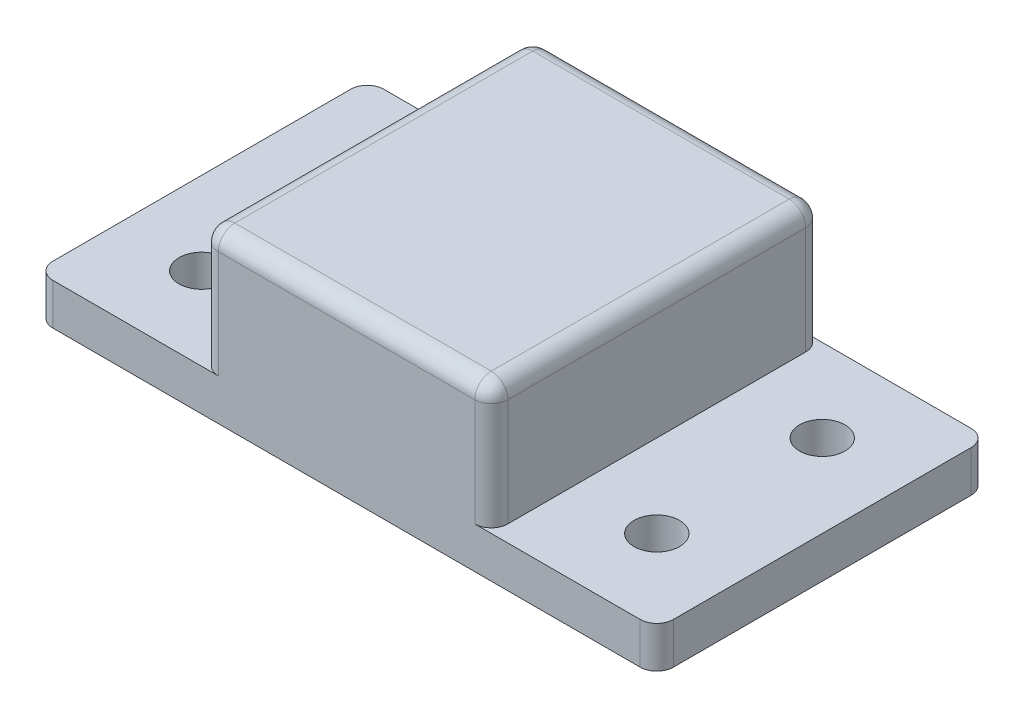
SolidWorks part; units mm, degrees
ref_plane "Front Plane" through (0, 0, 0) normal (0, 0, 1) x (1, 0, 0)
ref_plane "Top Plane" through (0, 0, 0) normal (0, 1, 0) x (1, 0, 0)
ref_plane "Right Plane" through (0, 0, 0) normal (1, 0, 0) x (0, 0, -1)
sketch "Sketch1" plane through (0, 0, 0) normal (0, 1, 0) x (1, 0, 0)
  line L1 (-37.5, 20) -> (37.5, 20)
  line L2 (-37.5, 20) -> (-37.5, -20)
  line L3 (-37.5, -20) -> (37.5, -20)
  line L4 (37.5, 20) -> (37.5, -20)
  line L5 (-37.5, 20) -> (37.5, -20) construction
  line L6 (-37.5, -20) -> (37.5, 20) construction
  point P0 (0, 0)
  dimension "D1" = 75
  dimension "D2" = 40
extrude "Boss-Extrude1" add sketch "Sketch1" along normal blind 5 contours L2 L3 L4 L1
sketch "Sketch3" plane through (0, 5, 0) normal (0, 1, 0) x (1, 0, 0)
  line L0 (-37.5, -20) -> (37.5, -20) construction
  line L1 (-17.5, 20) -> (17.5, 20)
  line L2 (-17.5, 20) -> (-17.5, -20)
  line L3 (-17.5, -20) -> (17.5, -20)
  line L4 (17.5, 20) -> (17.5, -20)
  line L5 (-17.5, 20) -> (17.5, -20) construction
  line L6 (-17.5, -20) -> (17.5, 20) construction
  line L7 (37.5, 20) -> (37.5, -20) construction
  point P0 (0, 0)
  dimension "D1" = 20
extrude "Boss-Extrude2" add sketch "Sketch3" along normal blind 15
fillet "Fillet1" radius 2 4 edges at (37.5, 2.5, 20) (37.5, 2.5, -20) (-37.5, 2.5, 20) (-37.5, 2.5, -20)
fillet "Fillet2" radius 2 8 edges at (0, 20, 20) (-17.5, 20, 0) (0, 20, -20) (17.5, 20, 0) (17.5, 12.5, -20) (-17.5, 12.5, -20) (-17.5, 12.5, 20) (17.5, 12.5, 20)
sketch "Sketch4" plane through (0, 0, 0) normal (0, -1, 0) x (1, 0, 0)
  line L0 (-37.5, 0) -> (-27.5, 0) construction
  line L1 (-37.5, -18) -> (-37.5, 18) construction
  line L2 (11, 0) -> (-11, 0) construction
  line L3 (-27.5, 10) -> (-27.5, -10) construction
  point P9 (-27.5, 0)
  dimension "D1" = 10
  dimension "D2" = 20
hole_wizard "M5 Clearance Hole1" positions "3DSketch1" profile "Sketch5" hole size "M5" standard "ANSI Metric" end condition through all
sketch3d "3DSketch1"
  point P0 (-27.5, 0, 10)
  point P3 (-27.5, 0, -10)
sketch "Sketch5" plane through (-27.5, 0, 10) normal (1, 0, 0) x (0, 0, -1)
  line L0 (0, 0) -> (0, 20)
  line L1 (0, 20) -> (2.75, 20)
  line L2 (2.75, 20) -> (2.75, 0.025)
  line L3 (2.75, 0.025) -> (2.775, 0)
  line L5 (2.775, 0) -> (0, 0)
  line L6 (-2.75, 0.025) -> (-2.775, 0) construction
  line L11 (0, -6.35) -> (0, 107.95) construction
  dimension "Thru Hole Dia." = 5.5
  dimension "Thru Hole Depth" = 20
  dimension "Near C'Sink Dia." = 5.55
  dimension "Near C'Sink Angle" = 90
mirror "Mirror1" about plane through (0, 0, 0) normal (1, 0, 0) of "M5 Clearance Hole1"
